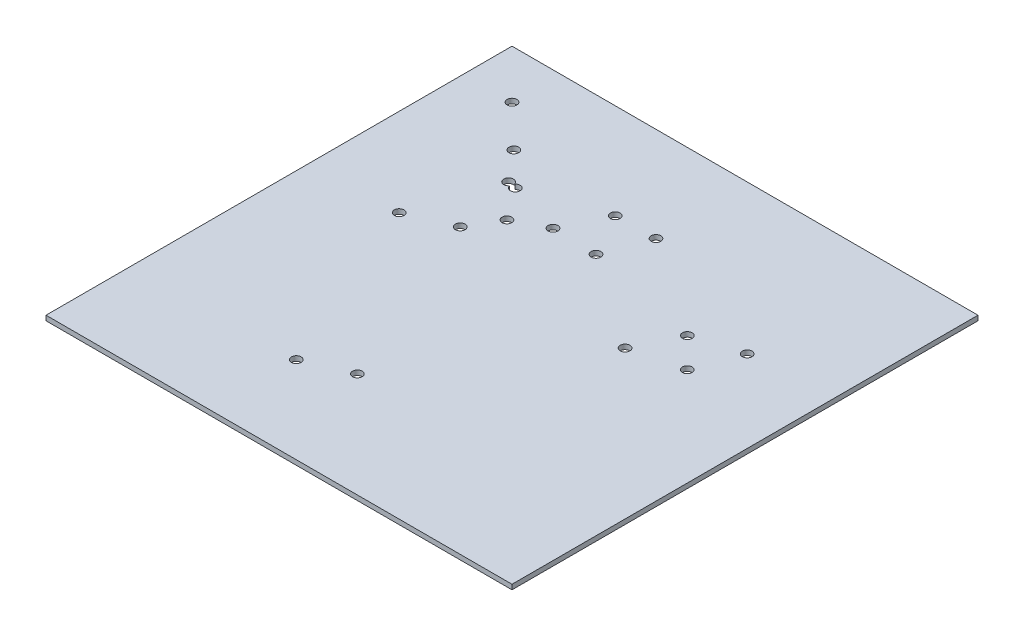
SolidWorks part; units mm, degrees
ref_plane "Front Plane" through (0, 0, 0) normal (0, 0, 1) x (1, 0, 0)
ref_plane "Top Plane" through (0, 0, 0) normal (0, 1, 0) x (1, 0, 0)
ref_plane "Right Plane" through (0, 0, 0) normal (1, 0, 0) x (0, 0, -1)
sketch "Sketch1" plane through (0, 0, 0) normal (0, 1, 0) x (1, 0, 0)
  line L0 (-120.65, 120.65) -> (-4.7472, -152.4) construction
  line L1 (152.4, -152.4) -> (-152.4, -152.4)
  line L2 (152.4, -152.4) -> (152.4, 152.4)
  line L3 (152.4, 152.4) -> (-152.4, 152.4)
  line L4 (-152.4, -152.4) -> (-152.4, 152.4)
  line L5 (152.4, -152.4) -> (-152.4, 152.4) construction
  line L6 (152.4, 152.4) -> (-152.4, -152.4) construction
  line L7 (-120.65, 120.65) -> (152.4, 18.7237) construction
  line L8 (-120.65, 120.65) -> (152.4, -11.5828) construction
  line L9 (-87.6508, 42.9087) -> (-38.2715, 89.8991) construction
  line L10 (-94.9802, 21.172) -> (-66.9232, 33.0814) construction
  line L11 (-45.3574, -95.7322) -> (-17.3004, -83.8227) construction
  line L12 (-22.566, 90.0829) -> (-35.851, 62.6504) construction
  line L13 (68.8755, 45.7996) -> (55.5905, 18.3671) construction
  line L14 (98.8448, 54.9824) -> (88.1855, 26.427) construction
  line L15 (3.6603, 90.5136) -> (-6.999, 61.9583) construction
  line L16 (-120.65, 120.65) -> (-134.1271, 152.4) construction
  line L17 (-120.65, 120.65) -> (139.1903, -152.4) construction
  line L18 (-120.65, 120.65) -> (152.4, -140.6016) construction
  line L19 (-66.1005, 100.2873) -> (-97.8992, 67.0526) construction
  line L20 (-93.0115, 94.2057) -> (-70.9883, 73.1342)
  line L21 (-55.6391, 52.3341) -> (-76.651, 74.4142)
  circle A0 centre (-120.65, 120.65) radius 3.175
  circle A1 centre (3.6603, 90.5136) radius 3.175
  circle A2 centre (-6.999, 61.9583) radius 3.175
  circle A3 centre (68.8755, 45.7996) radius 3.175
  circle A4 centre (98.8448, 54.9824) radius 3.175
  circle A5 centre (88.1855, 26.427) radius 3.175
  circle A6 centre (55.5905, 18.3671) radius 3.175
  circle A7 centre (-35.851, 62.6504) radius 3.175
  circle A8 centre (-22.566, 90.0829) radius 3.175
  circle A9 centre (-66.9232, 33.0814) radius 3.175
  circle A10 centre (-94.9802, 21.172) radius 3.175
  circle A11 centre (-17.3004, -83.8227) radius 3.175
  circle A12 centre (-45.3574, -95.7322) radius 3.175
  circle A17 centre (-120.65, 120.65) radius 12.7 construction
  circle A22 centre (-76.651, 74.4142) radius 3.175
  circle A23 centre (-70.9883, 73.1342) radius 3.175
  circle A24 centre (-55.6391, 52.3341) radius 3.175
  circle A25 centre (-93.0115, 94.2057) radius 3.175
  point P0 (0, 0)
  point P15 (-80.9517, 27.1267)
  point P18 (-31.3289, -89.7774)
  point P27 (-29.2085, 76.3667)
  point P28 (-1.6694, 76.236)
  point P29 (93.5152, 40.7047)
  point P30 (62.233, 32.0833)
  point P31 (-8.5024, -143.5533)
  point P46 (137.6722, -4.4504)
  point P58 (-81.9999, 83.67)
  point P59 (-66.145, 63.3741)
  dimension "D3" = 6.35
  dimension "D12" = 101.6
  dimension "D15" = 101.6
  dimension "D19" = 25.4
  dimension "D1" = 304.8
  dimension "D2" = 304.8
  dimension "D4" = 31.75
  dimension "D5" = 22
  dimension "D6" = 46.53
  dimension "D7" = 41.16
  dimension "D8" = 79.0653
  dimension "D9" = 30.48
  dimension "D10" = 287.02
  dimension "D11" = 287.02
  dimension "D13" = 101.6
  dimension "D14" = 127
  dimension "D16" = 101.6
  dimension "D17" = 127
  dimension "D20" = 20.58
  dimension "D21" = 23.265
  dimension "D22" = 53.4916
extrude "Boss-Extrude1" add sketch "Sketch1" along normal blind 3.175
